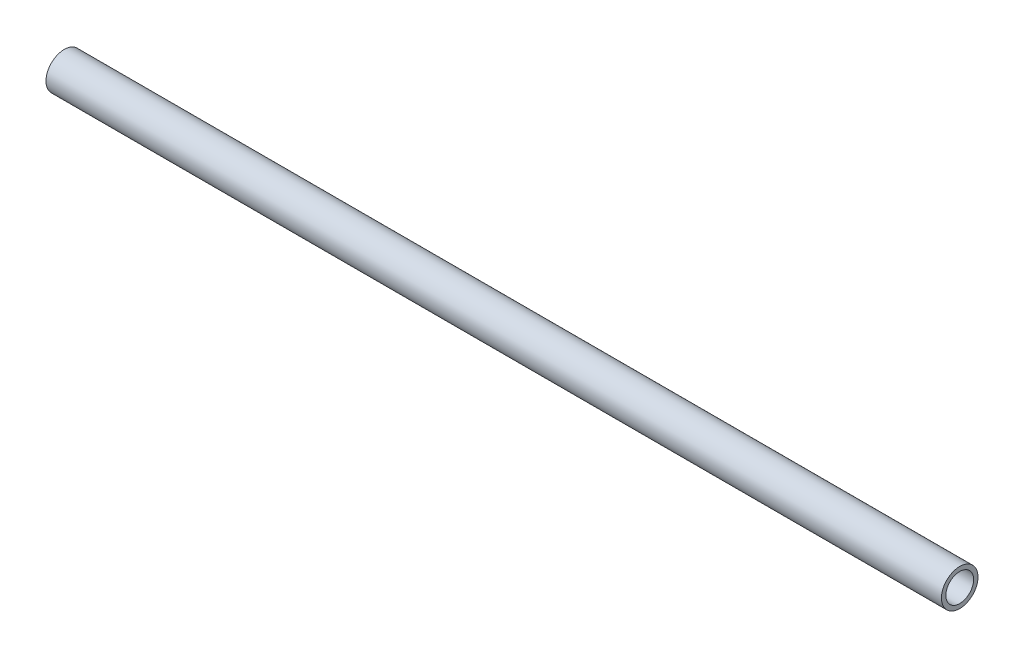
SolidWorks part; units mm, degrees
material "AISI 1010 Steel, hot rolled bar"
ref_plane "Front Plane" through (0, 0, 0) normal (0, 0, 1) x (1, 0, 0)
ref_plane "Top Plane" through (0, 0, 0) normal (0, 1, 0) x (1, 0, 0)
ref_plane "Right Plane" through (0, 0, 0) normal (1, 0, 0) x (0, 0, -1)
sketch "Sketch1" plane through (0, 0, 0) normal (1, 0, 0) x (0, 0, -1)
  circle A0 centre (0, 0) radius 12.7
  circle A1 centre (0, 0) radius 9.652
  dimension "D1" = 25.4
  dimension "D2" = 19.304
extrude "Boss-Extrude1" add sketch "Sketch1" along normal blind 622.3
